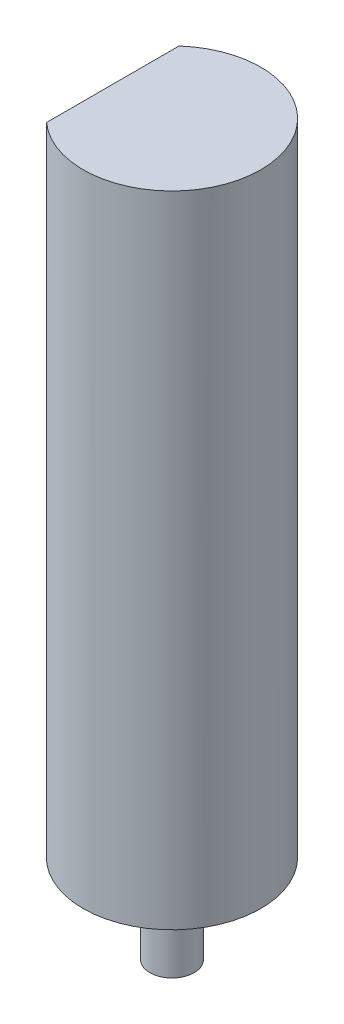
SolidWorks part; units mm, degrees
ref_plane "Спереди" through (0, 0, 0) normal (0, 0, 1) x (1, 0, 0)
ref_plane "Сверху" through (0, 0, 0) normal (0, 1, 0) x (1, 0, 0)
ref_plane "Справа" through (0, 0, 0) normal (1, 0, 0) x (0, 0, -1)
sketch "Эскиз1" plane through (0, 0, 0) normal (0, 1, 0) x (1, 0, 0)
  circle A0 centre (0, 0) radius 1.5
  dimension "D1" = 3
extrude "Бобышка-Вытянуть1" add sketch "Эскиз1" along normal blind 10.8
sketch "Эскиз2" plane through (0, 10.8, 0) normal (0, 1, 0) x (1, 0, 0)
  line L1 (-1.5, 0) -> (1.5, 0) construction
  line L3 (-1, -1.118) -> (-1, 1.118)
  circle A1 centre (0, 0) radius 1.5
  arc A2 (-1, 1.118) -> (-1, -1.118) centre (0, 0) ccw
  dimension "D1" = 0
extrude "Вырез-Вытянуть1" cut sketch "Эскиз2" against normal blind 6
sketch "Эскиз3" plane through (0, 0, 0) normal (0, -1, 0) x (1, 0, 0)
  circle A0 centre (0, 0) radius 0.375
  dimension "D1" = 0.75
extrude "Бобышка-Вытянуть2" add sketch "Эскиз3" along normal blind 1.5
